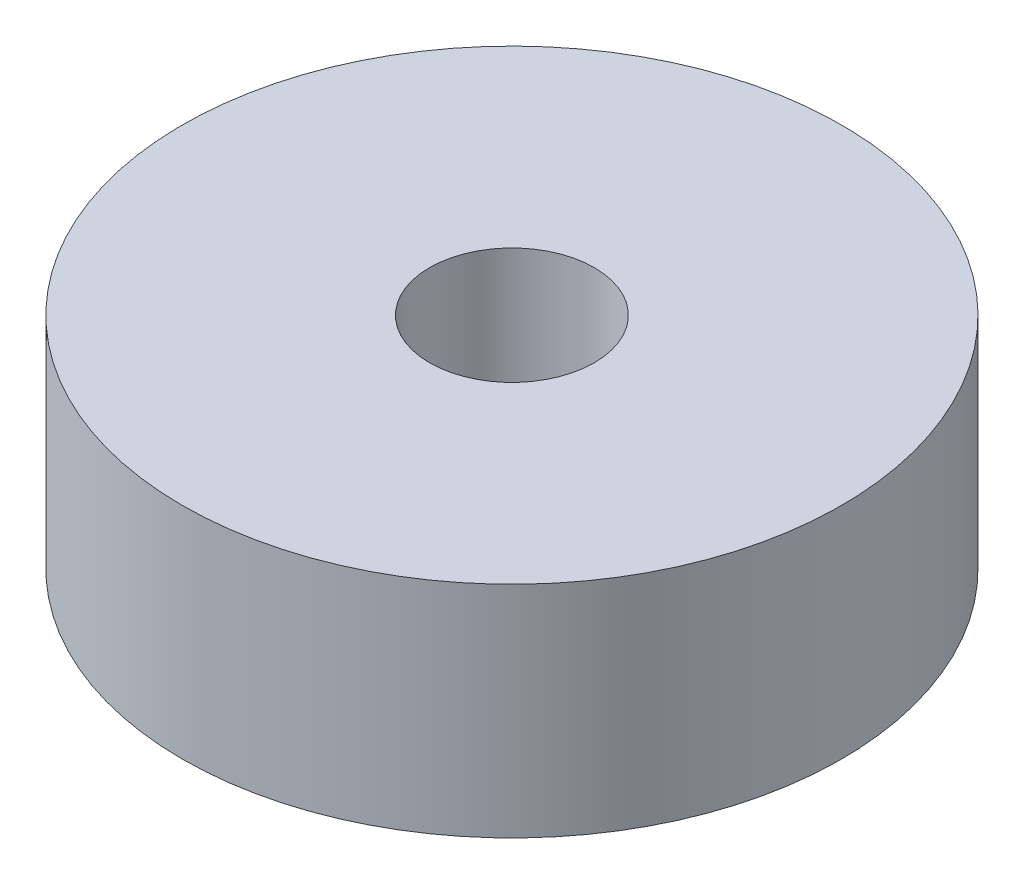
SolidWorks part; units mm, degrees
material "ABS"
ref_plane "Front Plane" through (0, 0, 0) normal (0, 0, 1) x (1, 0, 0)
ref_plane "Top Plane" through (0, 0, 0) normal (0, 1, 0) x (1, 0, 0)
ref_plane "Right Plane" through (0, 0, 0) normal (1, 0, 0) x (0, 0, -1)
sketch "Sketch1" plane through (0, 0, 0) normal (0, 1, 0) x (1, 0, 0)
  circle A0 centre (0, 0) radius 15
  dimension "D1" = 30
extrude "Boss-Extrude1" add sketch "Sketch1" along normal blind 10
sketch "Sketch2" plane through (0, 0, 0) normal (0, -1, 0) x (1, 0, 0)
  circle A0 centre (0, 0) radius 3.75
  dimension "D1" = 7.5
extrude "Cut-Extrude1" cut sketch "Sketch2" against normal blind 5
sketch "Sketch3" plane through (0, 10, 0) normal (0, 1, 0) x (1, 0, 0)
  circle A0 centre (0, 0) radius 3.75
  dimension "D1" = 7.5
extrude "Cut-Extrude2" cut sketch "Sketch3" against normal through all
